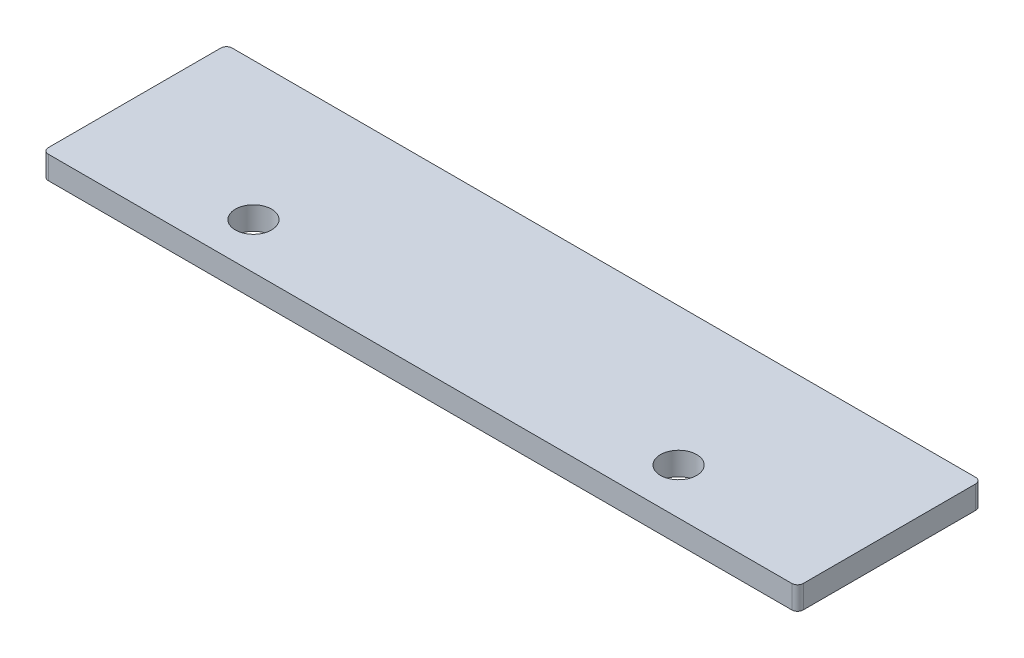
SolidWorks part; units mm, degrees
ref_plane "Спереди" through (0, 0, 0) normal (0, 0, 1) x (1, 0, 0)
ref_plane "Сверху" through (0, 0, 0) normal (0, 1, 0) x (1, 0, 0)
ref_plane "Справа" through (0, 0, 0) normal (1, 0, 0) x (0, 0, -1)
sketch "Эскиз1" plane through (0, 0, 0) normal (0, 1, 0) x (1, 0, 0)
  line L1 (-32.85, -8) -> (32.85, -8)
  line L2 (-32.85, -8) -> (-32.85, 8)
  line L3 (-32.85, 8) -> (32.85, 8)
  line L4 (32.85, -8) -> (32.85, 8)
  line L5 (-32.85, -8) -> (32.85, 8) construction
  line L6 (-32.85, 8) -> (32.85, -8) construction
  point P0 (0, 0)
  dimension "D1" = 65.7
  dimension "D2" = 16
extrude "Бобышка-Вытянуть1" add sketch "Эскиз1" against normal blind 2
fillet "Скругление1" radius 0.5 4 edges at (32.85, -1, -8) (32.85, -1, 8) (-32.85, -1, -8) (-32.85, -1, 8)
hole_wizard "Сверло под метчик  спиральное M31" positions "Эскиз3" profile "Эскиз5" hole size "M3x0.5" standard "DIN" end condition through all
sketch "Эскиз3" plane through (0, 0, 0) normal (0, 1, 0) x (1, 0, 0)
  line L0 (-32.85, -4) -> (32.85, -4) construction
  line L1 (-32.85, 7.5) -> (-32.85, -7.5) construction
  line L2 (32.85, -7.5) -> (32.85, 7.5) construction
  line L3 (-32.35, -8) -> (32.35, -8) construction
  point P9 (-18.5, -4)
  point P11 (18.5, -4)
  point P16 (0, -4)
  point P21 (14.6441, -5)
  dimension "D1" = 4
  dimension "D2" = 18.5
  dimension "D3" = 18.5
sketch "Эскиз5" plane through (18.5, 0, 4) normal (1, 0, 0) x (0, 0, 1)
  line L0 (0, 0) -> (0, 2)
  line L1 (0, 2) -> (1.575, 2)
  line L2 (1.575, 2) -> (1.575, 0)
  line L5 (1.575, 0) -> (0, 0)
  line L11 (0, -6.35) -> (0, 107.95) construction
  dimension "Диаметр сквозного отверстия" = 3.15
  dimension "Глубина сквозного отверстия" = 2
